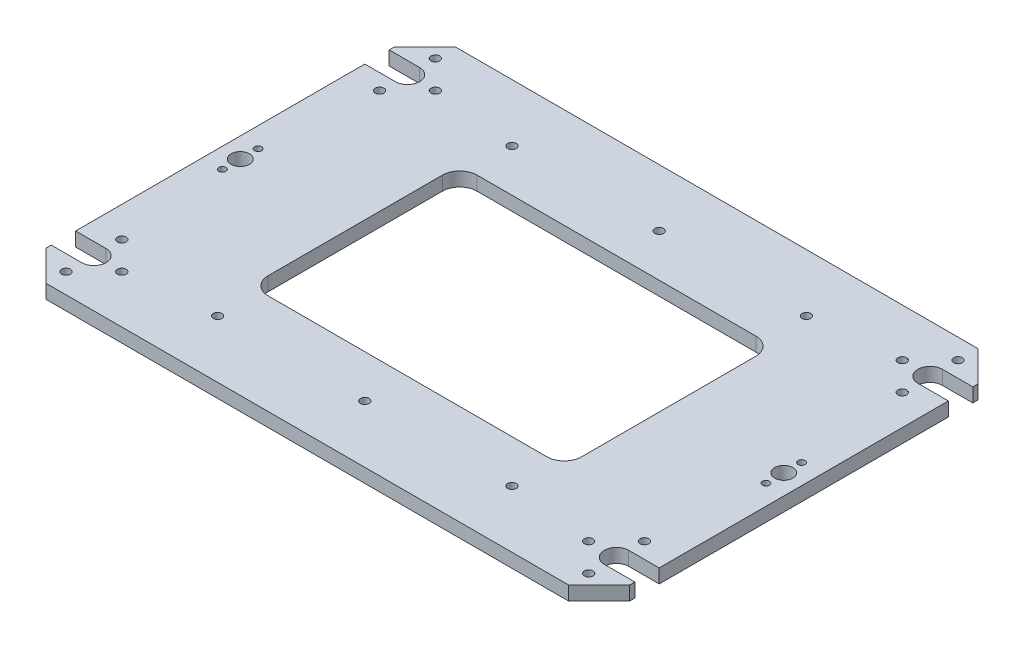
SolidWorks part; units mm, degrees
ref_plane "Front Plane" through (0, 0, 0) normal (0, 0, 1) x (1, 0, 0)
ref_plane "Top Plane" through (0, 0, 0) normal (0, 1, 0) x (1, 0, 0)
ref_plane "Right Plane" through (0, 0, 0) normal (1, 0, 0) x (0, 0, -1)
sketch "Sketch1" plane through (0, 0, 0) normal (0, 1, 0) x (1, 0, 0)
  line L0 (0, 84.5) -> (0, 117.5) construction
  line L1 (-167.5, -100) -> (-150, -117.5)
  line L4 (-150, -117.5) -> (150, -117.5)
  line L5 (-150, 117.5) -> (150, 117.5)
  line L6 (-156, -10.246) -> (-156, 10.246) construction
  line L7 (-127.5, -127.5) -> (127.5, -127.5) construction
  line L8 (-166, -90) -> (-150, -74) construction
  line L9 (0, 0) -> (0, -117.5) construction
  line L10 (-166, -90) -> (-150, -106) construction
  line L11 (-150, -74) -> (-134, -90) construction
  line L13 (-150, -106) -> (-134, -90) construction
  line L14 (-166, -90) -> (-134, -90) construction
  line L15 (-150, -74) -> (-150, -106) construction
  line L17 (-167.5, 0) -> (-156, 0) construction
  line L18 (-150, 117.5) -> (-167.5, 100)
  line L19 (-167.5, 100) -> (-167.5, 97)
  line L20 (-80, -60) -> (80, -60)
  line L21 (90, -50) -> (90, 50)
  line L22 (80, 60) -> (-80, 60)
  line L23 (-90, 50) -> (-90, -50)
  line L24 (-150, 90) -> (-150, -90) construction
  line L25 (-150, -83) -> (-167.5, -83)
  line L26 (-150, -97) -> (-167.5, -97)
  line L31 (-127.5, -127.5) -> (-127.5, 127.5) construction
  line L32 (-150, 97) -> (-167.5, 97)
  line L33 (-150, 83) -> (-167.5, 83)
  line L34 (-167.5, 97) -> (-167.5, 83) construction
  line L35 (-167.5, 83) -> (-167.5, -83)
  line L36 (-167.5, -83) -> (-167.5, -97) construction
  line L37 (-167.5, -97) -> (-167.5, -100)
  line L38 (150, 117.5) -> (167.5, 100)
  line L39 (167.5, 100) -> (167.5, 97)
  line L40 (-127.5, 127.5) -> (127.5, 127.5) construction
  line L41 (-84.5, 84.5) -> (84.5, 84.5) construction
  line L42 (84.5, 84.5) -> (84.5, -84.5) construction
  line L43 (84.5, -84.5) -> (-84.5, -84.5) construction
  line L44 (-84.5, -84.5) -> (-84.5, 84.5) construction
  line L45 (-84.5, 0) -> (0, 0) construction
  line L46 (0, 0) -> (0, 84.5) construction
  line L47 (127.5, -127.5) -> (127.5, 127.5) construction
  line L48 (-127.5, -127.5) -> (127.5, 127.5) construction
  line L49 (-127.5, 127.5) -> (127.5, -127.5) construction
  line L50 (150, 97) -> (167.5, 97)
  line L51 (150, 83) -> (167.5, 83)
  line L52 (167.5, 83) -> (167.5, -83)
  line L53 (167.5, -97) -> (167.5, -100)
  line L54 (167.5, -100) -> (150, -117.5)
  line L55 (150, -97) -> (167.5, -97)
  line L56 (150, -83) -> (167.5, -83)
  arc A5 (80, -60) -> (90, -50) centre (80, -50) ccw
  arc A6 (90, 50) -> (80, 60) centre (80, 50) ccw
  arc A7 (-80, 60) -> (-90, 50) centre (-80, 50) ccw
  arc A8 (-90, -50) -> (-80, -60) centre (-80, -50) ccw
  circle A14 centre (-156, 0) radius 5.25
  circle A15 centre (-156, -10.246) radius 2
  circle A16 centre (-84.5, 84.5) radius 2.5
  circle A17 centre (0, 84.5) radius 2.5
  circle A18 centre (84.5, 84.5) radius 2.5
  circle A24 centre (84.5, -84.5) radius 2.5
  circle A25 centre (0, -84.5) radius 2.5
  circle A26 centre (-84.5, -84.5) radius 2.5
  arc A31 (-150, -97) -> (-150, -83) centre (-150, -90) ccw
  circle A32 centre (-156, 10.246) radius 2
  circle A37 centre (-150, -90) radius 16 construction
  arc A56 (150, 97) -> (150, 83) centre (150, 90) ccw
  circle A63 centre (156, 10.246) radius 2
  circle A64 centre (156, -10.246) radius 2
  circle A65 centre (156, 0) radius 5.25
  circle A66 centre (-150, -74) radius 2.5
  circle A67 centre (-134, -90) radius 2.5
  circle A68 centre (-150, -106) radius 2.5
  circle A69 centre (-150, 74) radius 2.5
  circle A70 centre (-134, 90) radius 2.5
  circle A71 centre (-150, 106) radius 2.5
  arc A72 (-150, 97) -> (-150, 83) centre (-150, 90) cw
  arc A74 (150, -97) -> (150, -83) centre (150, -90) cw
  circle A75 centre (150, -74) radius 2.5
  circle A76 centre (134, -90) radius 2.5
  circle A77 centre (150, -106) radius 2.5
  arc A78 (150, -83) -> (150, -97) centre (150, -90) cw construction
  arc A79 (-150, 83) -> (-150, 97) centre (-150, 90) cw construction
  circle A80 centre (150, 106) radius 2.5
  circle A81 centre (150, 74) radius 2.5
  circle A82 centre (134, 90) radius 2.5
  point P10 (148.8976, 97)
  point P18 (0, 0)
  point P25 (-160.3846, -109.5364)
  point P28 (-130.3678, -117.5)
  point P29 (-145.4339, -117.5)
  point P30 (-160.2522, -106)
  point P31 (-150, -117.5)
  point P32 (-160.815, -107.7291)
  point P33 (-170.2673, -100.2215)
  point P36 (-150, -117.5)
  point P37 (-167.472, -100.028)
  point P70 (0, 0)
  point P103 (0, -60)
  dimension "D3" = 180
  dimension "D6" = 10
  dimension "D8" = 10.246
  dimension "D9" = 4
  dimension "D10" = 10.5
  dimension "D12" = 5
  dimension "D13" = 14
  dimension "D15" = 5
  dimension "D16" = 200
  dimension "D7" = 32
  dimension "D2" = 235
  dimension "D4" = 180
  dimension "D5" = 120
  dimension "D11" = 300
  dimension "D14" = 169
  dimension "D17" = 255
  dimension "D18" = 6
extrude "Boss-Extrude1" add sketch "Sketch1" along normal blind 8
sketch "Sketch2" plane through (0, 8, 0) normal (0, 1, 0) x (1, 0, 0)
  circle A0 centre (-84.5, -84.5) radius 2.5 construction
  circle A1 centre (0, -84.5) radius 2.5 construction
  circle A2 centre (84.5, -84.5) radius 2.5 construction
  circle A3 centre (84.5, 84.5) radius 2.5 construction
  circle A4 centre (0, 84.5) radius 2.5 construction
  circle A5 centre (-84.5, 84.5) radius 2.5 construction
  circle A6 centre (-84.5, -84.5) radius 2.5
  circle A7 centre (0, -84.5) radius 2.5
  circle A8 centre (84.5, -84.5) radius 2.5
  circle A9 centre (84.5, 84.5) radius 2.5
  circle A10 centre (0, 84.5) radius 2.5
  circle A11 centre (-84.5, 84.5) radius 2.5
  circle A12 centre (-84.5, -84.5) radius 8
  circle A13 centre (0, -84.5) radius 8
  circle A14 centre (84.5, -84.5) radius 8
  circle A15 centre (84.5, 84.5) radius 8
  circle A16 centre (0, 84.5) radius 8
  circle A17 centre (-84.5, 84.5) radius 8
  dimension "D1" = 16
extrude "Cut-Extrude1" [suppressed] cut sketch "Sketch2" against normal blind 3
